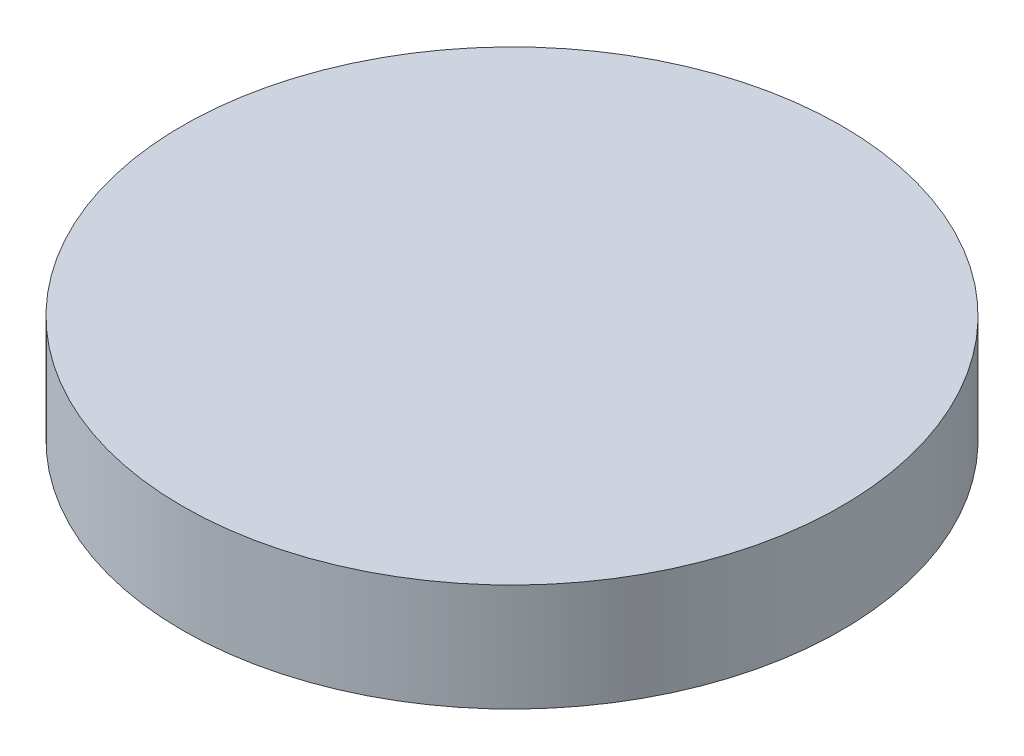
SolidWorks part; units mm, degrees
ref_plane "Front Plane" through (0, 0, 0) normal (0, 0, 1) x (1, 0, 0)
ref_plane "Top Plane" through (0, 0, 0) normal (0, 1, 0) x (1, 0, 0)
ref_plane "Right Plane" through (0, 0, 0) normal (1, 0, 0) x (0, 0, -1)
sketch "Sketch1" plane through (0, 0, 0) normal (0, 1, 0) x (1, 0, 0)
  circle A0 centre (0, 0) radius 67.5
  dimension "D1" = 135
extrude "Boss-Extrude1" add sketch "Sketch1" along normal blind 22
